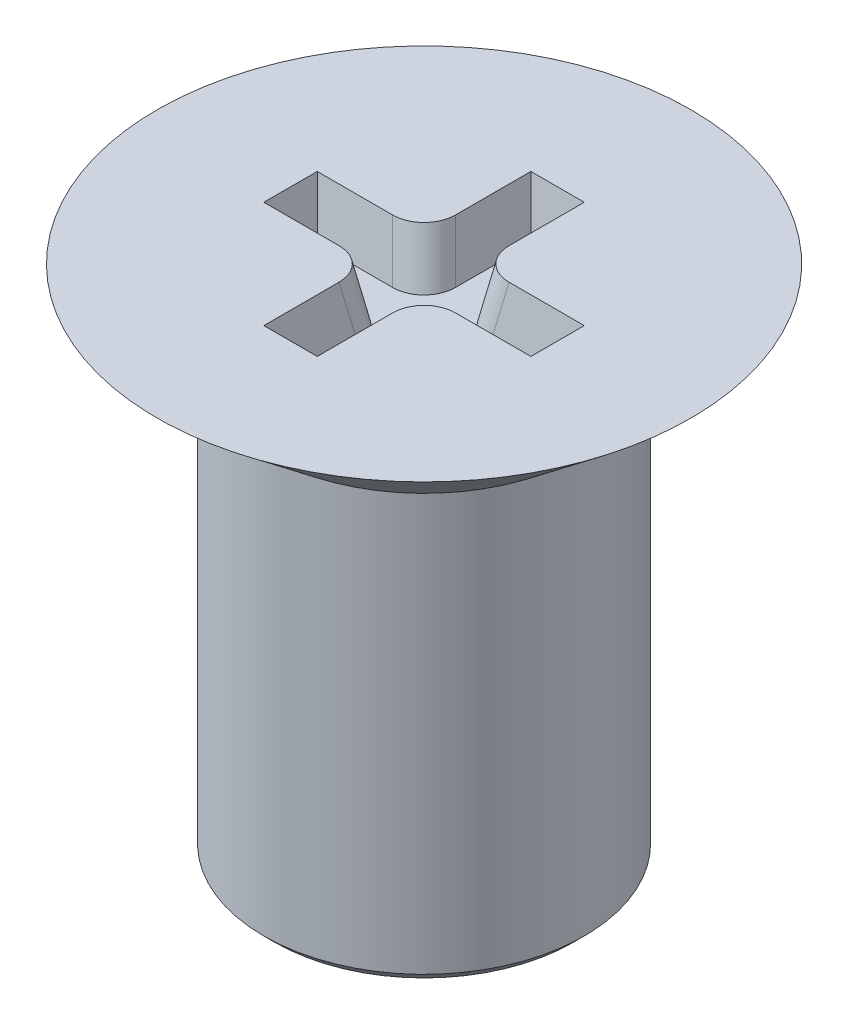
SolidWorks part; units mm, degrees
material "AISI 321 退火不锈钢 (SS)"
ref_plane "前视基准面" through (0, 0, 0) normal (0, 0, 1) x (1, 0, 0)
ref_plane "上视基准面" through (0, 0, 0) normal (0, 1, 0) x (1, 0, 0)
ref_plane "右视基准面" through (0, 0, 0) normal (1, 0, 0) x (0, 0, -1)
other "Configuration Table"
sketch "草图1" plane through (0, 0, 0) normal (0, 0, 1) x (1, 0, 0)
  line L0 (0, 0) -> (2.5, 0)
  line L1 (2.5, 0) -> (1.5, -0.8)
  line L2 (1.5, -0.8) -> (0, -0.8)
  line L3 (0, -0.8) -> (0, 0)
  dimension "D1" = 2.5
  dimension "D2" = 0.8
  dimension "D3" = 1.5
revolve "旋转1" add sketch "草图1" angle 360 about L3
sketch "草图2" plane through (0, -0.8, 0) normal (0, -1, 0) x (1, 0, 0)
  circle A1 centre (0, 0) radius 1.5
  circle A2 centre (0, 0) radius 1.5
  dimension "D1" = 0
extrude "凸台-拉伸1" add sketch "草图2" along normal blind 4
cosmetic thread "装饰螺纹线1" parameters "D2"=2.459
chamfer "倒角1" distance 0.1 angle 45 1 edges at (0, -4.8, -1.5)
sketch "草图3" plane through (0, 0, 0) normal (0, 1, 0) x (1, 0, 0)
  line L1 (-1.25, -0.25) -> (1.25, -0.25)
  line L2 (-1.25, -0.25) -> (-1.25, 0.25)
  line L3 (-1.25, 0.25) -> (1.25, 0.25)
  line L4 (1.25, -0.25) -> (1.25, 0.25)
  line L5 (-1.25, -0.25) -> (1.25, 0.25) construction
  line L6 (-1.25, 0.25) -> (1.25, -0.25) construction
  line L7 (-0.25, 1.25) -> (0.25, 1.25)
  line L8 (-0.25, 1.25) -> (-0.25, -1.25)
  line L9 (-0.25, -1.25) -> (0.25, -1.25)
  line L10 (0.25, 1.25) -> (0.25, -1.25)
  line L11 (-0.25, 1.25) -> (0.25, -1.25) construction
  line L12 (-0.25, -1.25) -> (0.25, 1.25) construction
  point P0 (0, 0)
  point P6 (0, 0)
  dimension "D1" = 0.5
  dimension "D2" = 0.5
  dimension "D3" = 2.5
  dimension "D4" = 2.5
extrude "切除-拉伸1" cut sketch "草图3" against normal blind 0.5 draft 10 contours L3 L10 L1 L4 | L10 L7 L8 L3 | L8 L3 L2 L1 | L10 L3 L8 L1 | L10 L1 L8 L9
fillet "圆角1" radius 0.3 4 edges at (-0.2059, -0.25, -0.2059) (0.2059, -0.25, -0.2059) (-0.2059, -0.25, 0.2059) (0.2059, -0.25, 0.2059)
